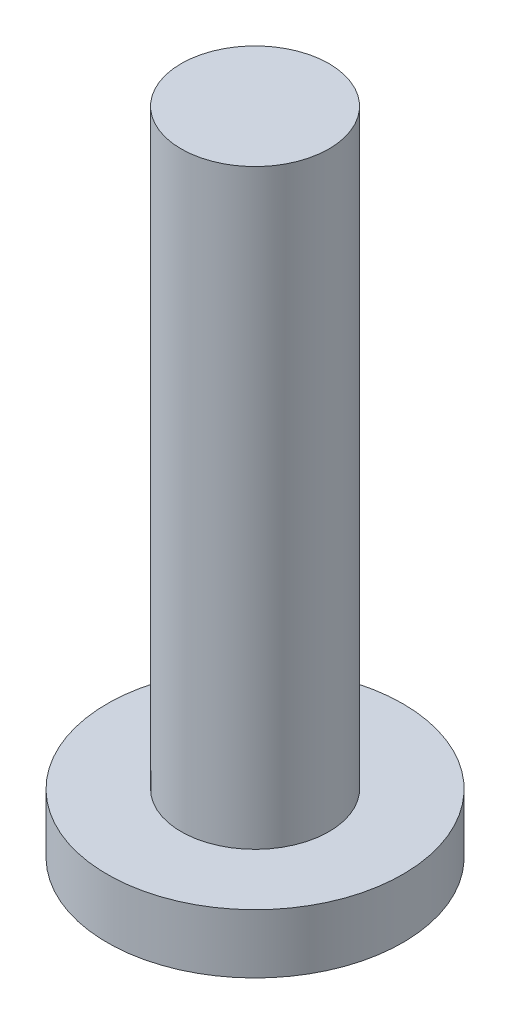
SolidWorks part; units mm, degrees
ref_plane "Front Plane" through (0, 0, 0) normal (0, 0, 1) x (1, 0, 0)
ref_plane "Top Plane" through (0, 0, 0) normal (0, 1, 0) x (1, 0, 0)
ref_plane "Right Plane" through (0, 0, 0) normal (1, 0, 0) x (0, 0, -1)
sketch "Sketch1" plane through (0, 0, 0) normal (0, 1, 0) x (1, 0, 0)
  circle A0 centre (0, 0) radius 1.25
  dimension "D1" = 2.5
extrude "Boss-Extrude1" add sketch "Sketch1" along normal blind 10
sketch "Sketch2" plane through (0, 0, 0) normal (0, -1, 0) x (1, 0, 0)
  circle A0 centre (0, 0) radius 2.5
extrude "Boss-Extrude2" add sketch "Sketch2" along normal blind 1
